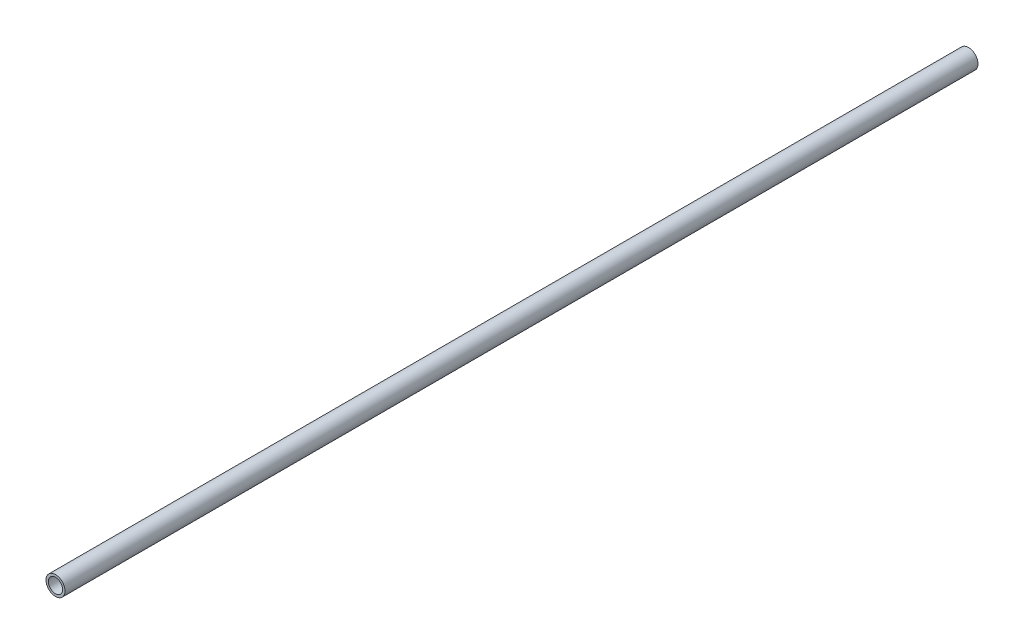
SolidWorks part; units mm, degrees
ref_plane "Front Plane" through (0, 0, 0) normal (0, 0, 1) x (1, 0, 0)
ref_plane "Top Plane" through (0, 0, 0) normal (0, 1, 0) x (1, 0, 0)
ref_plane "Right Plane" through (0, 0, 0) normal (1, 0, 0) x (0, 0, -1)
sketch "Sketch1" plane through (0, 0, 0) normal (0, 0, 1) x (1, 0, 0)
  circle A0 centre (0, 0) radius 9.525
  circle A1 centre (0, 0) radius 7.1438
  dimension "D1" = 19.05
  dimension "D2" = 14.2875
extrude "Boss-Extrude1" add sketch "Sketch1" along normal blind 914.4
equation "\"span\"= 48"
equation "\"wing_chord\"= 9"
equation "\"fuse_len\"= 15"
equation "\"fuse_height\"= 5"
equation "\"fuse_wid\"= 5"
equation "\"foam_t\"= 0.1875"
equation "\"main_spar_len\"= 36"
equation "\"D1@Boss-Extrude1\"= \"main_spar_len\""
